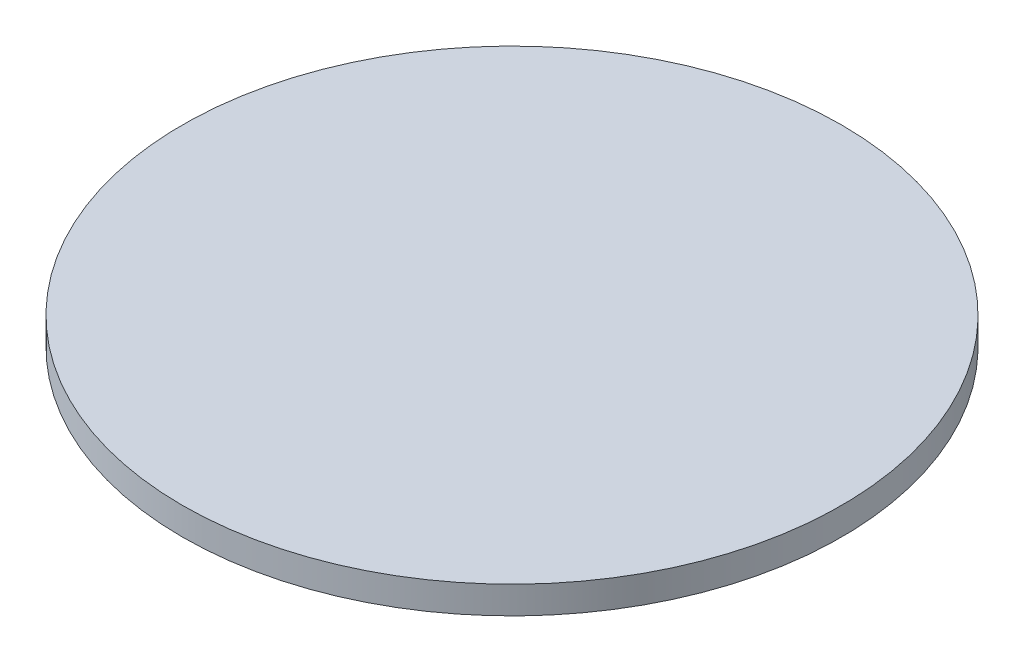
SolidWorks part; units mm, degrees
ref_plane "Front Plane" through (0, 0, 0) normal (0, 0, 1) x (1, 0, 0)
ref_plane "Top Plane" through (0, 0, 0) normal (0, 1, 0) x (1, 0, 0)
ref_plane "Right Plane" through (0, 0, 0) normal (1, 0, 0) x (0, 0, -1)
sketch "Sketch1" plane through (0, 0, 0) normal (0, 1, 0) x (1, 0, 0)
  circle A0 centre (0, 0) radius 152.4
  dimension "D1" = 304.8
extrude "Extrude1" add sketch "Sketch1" along normal blind 12.7
